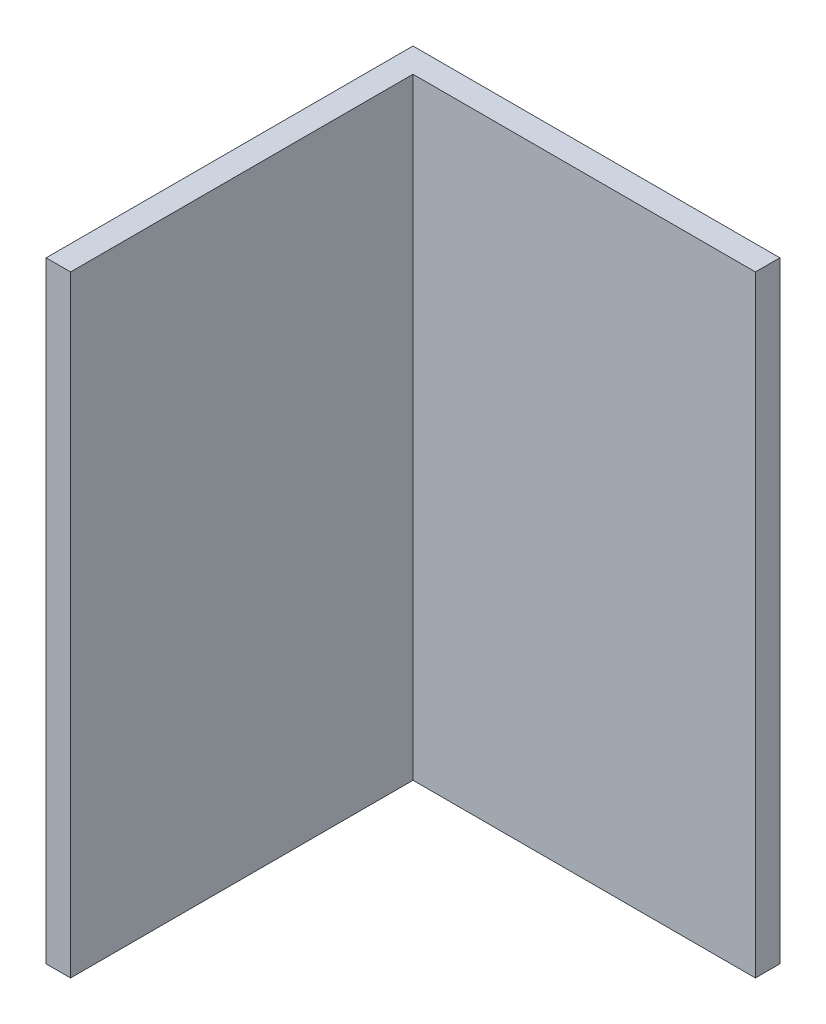
SolidWorks part; units mm, degrees
ref_plane "Plan de face" through (0, 0, 0) normal (0, 0, 1) x (1, 0, 0)
ref_plane "Plan de dessus" through (0, 0, 0) normal (0, 1, 0) x (1, 0, 0)
ref_plane "Plan de droite" through (0, 0, 0) normal (1, 0, 0) x (0, 0, -1)
sketch "Esquisse1" plane through (0, 0, 0) normal (0, 0, 1) x (1, 0, 0)
  line L1 (0, 0) -> (30, 0)
  line L2 (0, 0) -> (0, 50)
  line L3 (0, 50) -> (30, 50)
  line L4 (30, 0) -> (30, 50)
  dimension "D1" = 30
  dimension "D2" = 50
extrude "Boss.-Extru.1" add sketch "Esquisse1" along normal blind 2
sketch "Esquisse2" plane through (0, 0, 2) normal (0, 0, 1) x (1, 0, 0)
  line L0 (0, 0) -> (30, 0) construction
  line L1 (0, 50) -> (2, 50)
  line L2 (0, 50) -> (0, 0)
  line L3 (0, 0) -> (2, 0)
  line L4 (2, 50) -> (2, 0)
  dimension "D1" = 2
extrude "Boss.-Extru.2" add sketch "Esquisse2" along normal blind 28
